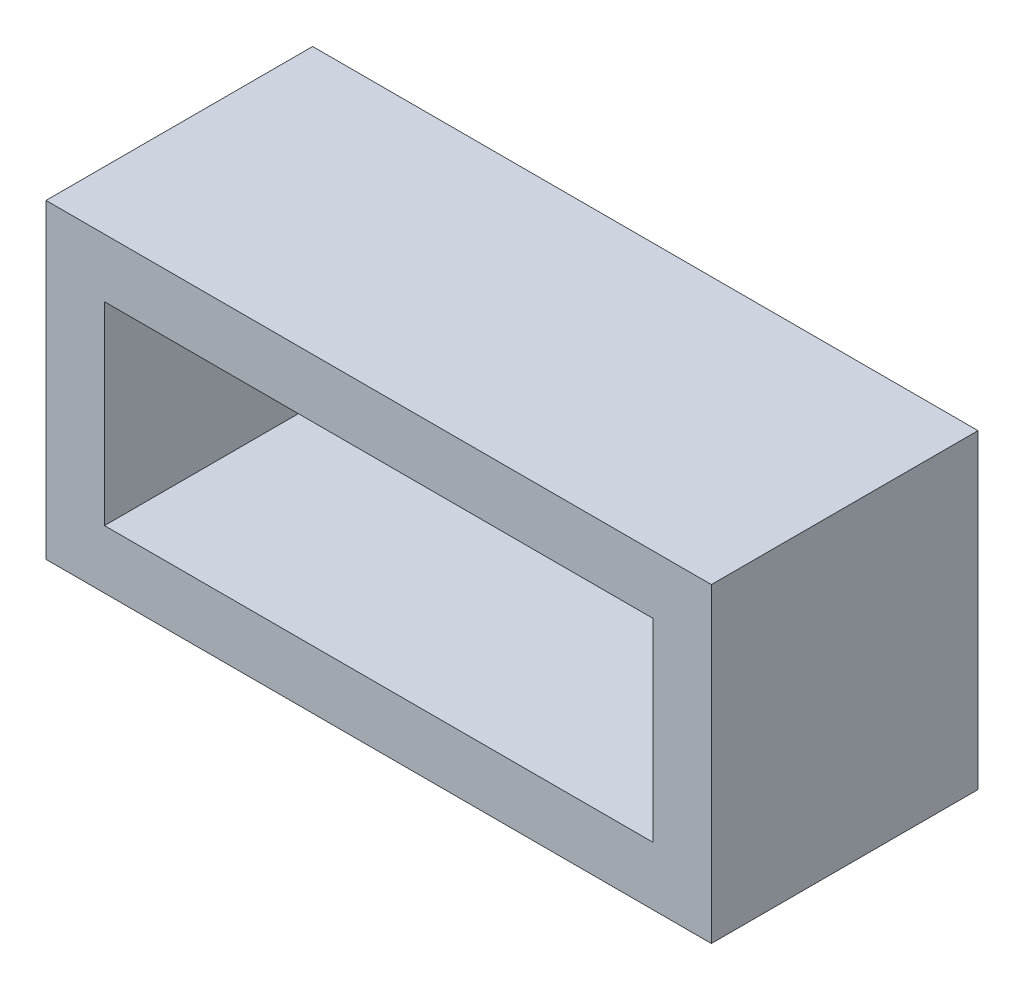
SolidWorks part; units mm, degrees
ref_plane "정면" through (0, 0, 0) normal (0, 0, 1) x (1, 0, 0)
ref_plane "윗면" through (0, 0, 0) normal (0, 1, 0) x (1, 0, 0)
ref_plane "우측면" through (0, 0, 0) normal (1, 0, 0) x (0, 0, -1)
sketch "스케치1" plane through (0, 0, 0) normal (0, 0, 1) x (1, 0, 0)
  line L0 (-23.601, -1.0242) -> (23.8623, -0.5888) construction
  line L1 (0, 27.35) -> (0, -24.2613) construction
  line L2 (-10.8494, 4.3235) -> (11.1106, 4.3235)
  line L3 (-8.9194, 2.3935) -> (9.1806, 2.3935)
  line L4 (-8.9194, 2.3935) -> (-8.9194, -4.0065)
  line L5 (-8.9194, -4.0065) -> (9.1806, -4.0065)
  line L6 (9.1806, 2.3935) -> (9.1806, -4.0065)
  line L7 (-8.9194, 2.3935) -> (9.1806, -4.0065) construction
  line L8 (-8.9194, -4.0065) -> (9.1806, 2.3935) construction
  line L9 (11.1106, 4.3235) -> (11.1106, -5.9365)
  line L10 (-10.8494, -5.9365) -> (11.1106, -5.9365)
  line L11 (-10.8494, 4.3235) -> (-10.8494, -5.9365)
  point P6 (0.1306, -0.8065)
  dimension "D1" = 18.1
  dimension "D2" = 6.4
  dimension "D3" = 1.93
extrude "보스-돌출1" add sketch "스케치1" along normal blind 8.8
